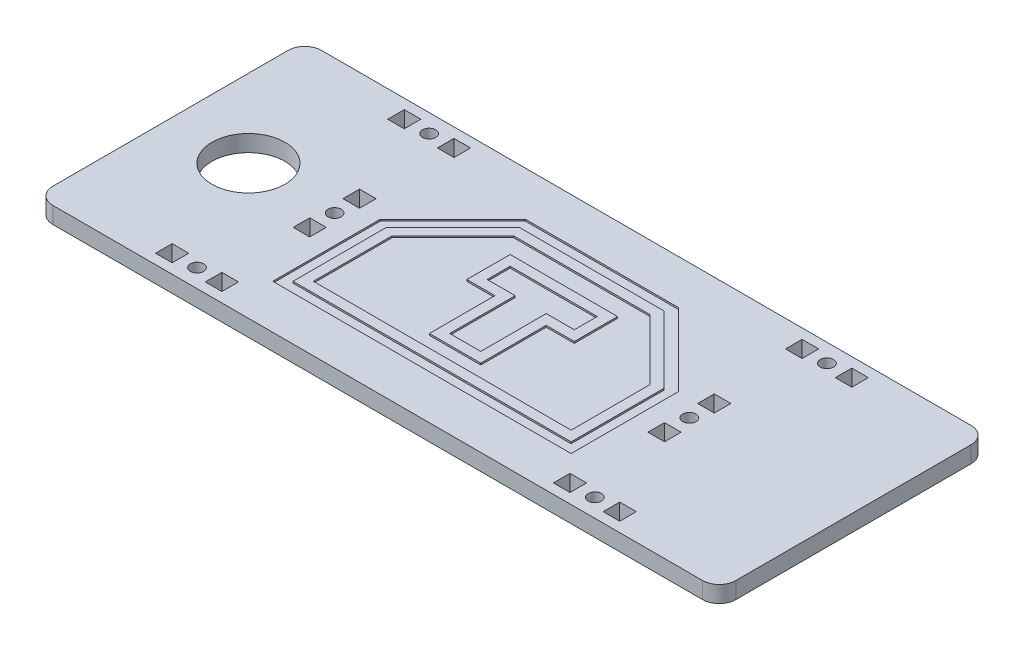
SolidWorks part; units mm, degrees
ref_plane "Front Plane" through (0, 0, 0) normal (0, 0, 1) x (1, 0, 0)
ref_plane "Top Plane" through (0, 0, 0) normal (0, 1, 0) x (1, 0, 0)
ref_plane "Right Plane" through (0, 0, 0) normal (1, 0, 0) x (0, 0, -1)
sketch "Sketch1" plane through (0, 0, 0) normal (0, 1, 0) x (1, 0, 0)
  line L0 (5.1027, 53.6563) -> (5.1027, -27.3437) construction
  line L1 (-97.8973, 53.6563) -> (108.1027, 53.6563)
  line L2 (-97.8973, 53.6563) -> (-97.8973, -27.3437)
  line L3 (-97.8973, -27.3437) -> (108.1027, -27.3437)
  line L4 (108.1027, 53.6563) -> (108.1027, -27.3437)
  line L5 (-97.8973, 13.1563) -> (108.1027, 13.1563) construction
  line L6 (60.1027, 45.6563) -> (55.1027, 45.6563)
  line L7 (-64.8973, 50.6563) -> (-59.8973, 50.6563)
  line L8 (-64.8973, 50.6563) -> (-64.8973, 45.6563)
  line L9 (-64.8973, 45.6563) -> (-59.8973, 45.6563)
  line L10 (-59.8973, 50.6563) -> (-59.8973, 45.6563)
  line L11 (-49.8973, 50.6563) -> (-44.8973, 50.6563)
  line L12 (-49.8973, 50.6563) -> (-49.8973, 45.6563)
  line L13 (-49.8973, 45.6563) -> (-44.8973, 45.6563)
  line L14 (-44.8973, 50.6563) -> (-44.8973, 45.6563)
  line L15 (55.1027, 50.6563) -> (55.1027, 45.6563)
  line L16 (60.1027, 50.6563) -> (55.1027, 50.6563)
  line L17 (60.1027, 50.6563) -> (60.1027, 45.6563)
  line L18 (70.1027, 50.6563) -> (70.1027, 45.6563)
  line L19 (75.1027, 50.6563) -> (70.1027, 50.6563)
  line L20 (75.1027, 50.6563) -> (75.1027, 45.6563)
  line L21 (75.1027, 45.6563) -> (70.1027, 45.6563)
  line L22 (75.1027, -24.3437) -> (75.1027, -19.3437)
  line L23 (75.1027, -19.3437) -> (70.1027, -19.3437)
  line L24 (75.1027, -24.3437) -> (70.1027, -24.3437)
  line L25 (70.1027, -24.3437) -> (70.1027, -19.3437)
  line L26 (60.1027, -24.3437) -> (60.1027, -19.3437)
  line L27 (60.1027, -19.3437) -> (55.1027, -19.3437)
  line L28 (55.1027, -24.3437) -> (55.1027, -19.3437)
  line L29 (60.1027, -24.3437) -> (55.1027, -24.3437)
  line L30 (-49.8973, -24.3437) -> (-44.8973, -24.3437)
  line L31 (-44.8973, -24.3437) -> (-44.8973, -19.3437)
  line L32 (-49.8973, -19.3437) -> (-44.8973, -19.3437)
  line L33 (-49.8973, -24.3437) -> (-49.8973, -19.3437)
  line L34 (-64.8973, -24.3437) -> (-59.8973, -24.3437)
  line L35 (-64.8973, -24.3437) -> (-64.8973, -19.3437)
  line L36 (-64.8973, -19.3437) -> (-59.8973, -19.3437)
  line L37 (-59.8973, -24.3437) -> (-59.8973, -19.3437)
  line L42 (-45.8973, 18.1563) -> (-45.8973, 23.1563)
  line L43 (-50.8973, 8.1563) -> (-45.8973, 8.1563)
  line L44 (-50.8973, 8.1563) -> (-50.8973, 3.1563)
  line L45 (-50.8973, 3.1563) -> (-45.8973, 3.1563)
  line L46 (-45.8973, 8.1563) -> (-45.8973, 3.1563)
  line L47 (-50.8973, 23.1563) -> (-45.8973, 23.1563)
  line L48 (-50.8973, 18.1563) -> (-50.8973, 23.1563)
  line L49 (-50.8973, 18.1563) -> (-45.8973, 18.1563)
  line L50 (56.1027, 8.1563) -> (56.1027, 3.1563)
  line L51 (61.1027, 3.1563) -> (56.1027, 3.1563)
  line L52 (61.1027, 8.1563) -> (61.1027, 3.1563)
  line L53 (61.1027, 8.1563) -> (56.1027, 8.1563)
  line L54 (56.1027, 18.1563) -> (56.1027, 23.1563)
  line L55 (61.1027, 18.1563) -> (56.1027, 18.1563)
  line L56 (61.1027, 18.1563) -> (61.1027, 23.1563)
  line L57 (61.1027, 23.1563) -> (56.1027, 23.1563)
  circle A0 centre (-54.8973, 48.1563) radius 2
  circle A1 centre (-54.8973, -21.8437) radius 2
  circle A2 centre (65.1027, -21.8437) radius 2
  circle A3 centre (65.1027, 48.1563) radius 2
  circle A5 centre (-48.3973, 13.1563) radius 2
  circle A6 centre (58.6027, 13.1563) radius 2
  circle A7 centre (-74.3973, 13.1563) radius 11
  point P36 (-59.8973, -19.3437)
  point P55 (-45.8973, 5.6563)
  dimension "D7" = 4
  dimension "D8" = 4
  dimension "D12" = 22
  dimension "D1" = 206
  dimension "D2" = 81
  dimension "D3" = 5
  dimension "D4" = 10
  dimension "D5" = 3
  dimension "D6" = 50
  dimension "D9" = 51
  dimension "D10" = 5
  dimension "D11" = 5.5
extrude "Boss-Extrude1" add sketch "Sketch1" along normal blind 5
fillet "Fillet1" radius 5 4 edges at (108.1027, 2.5, 27.3437) (-97.8973, 2.5, 27.3437) (-97.8973, 2.5, -53.6563) (108.1027, 2.5, -53.6563)
sketch "Sketch2" plane through (0, 5, 0) normal (0, 1, 0) x (1, 0, 0)
  line L0 (5.1027, 53.6563) -> (5.1027, -27.3437) construction
  line L1 (103.1027, 53.6563) -> (-92.8973, 53.6563) construction
  line L2 (-92.8973, -27.3437) -> (103.1027, -27.3437) construction
  line L3 (-97.8973, 13.1563) -> (108.1027, 13.1563) construction
  line L4 (-97.8973, 48.6563) -> (-97.8973, -22.3437) construction
  line L5 (108.1027, -22.3437) -> (108.1027, 48.6563) construction
  line L6 (-39.8973, -14.0037) -> (50.1027, -14.0037)
  line L7 (50.1027, -14.0037) -> (50.1027, 18.3963)
  line L8 (50.1027, 18.3963) -> (28.1877, 40.3113)
  line L9 (5.1027, -14.0037) -> (5.1027, -19.0236) construction
  line L10 (-39.8973, -14.0037) -> (-39.8973, 18.3963)
  line L11 (-39.8973, 18.3963) -> (-17.9823, 40.3113)
  line L12 (-17.9823, 40.3113) -> (28.1877, 40.3113)
  line L13 (47.0427, 17.1288) -> (47.0427, -10.9437)
  line L14 (47.0427, -10.9437) -> (-36.8373, -10.9437)
  line L15 (47.0427, 17.1288) -> (26.9202, 37.2513)
  line L16 (26.9202, 37.2513) -> (-16.7148, 37.2513)
  line L17 (43.9827, 15.8613) -> (43.9827, -7.8837)
  line L18 (43.9827, -7.8837) -> (-33.7773, -7.8837)
  line L19 (43.9827, 15.8613) -> (25.6527, 34.1913)
  line L20 (25.6527, 34.1913) -> (-15.4473, 34.1913)
  line L21 (-8.0373, 25.7313) -> (18.2427, 25.7313)
  line L22 (-11.0973, 28.7913) -> (21.3027, 28.7913)
  line L23 (21.3027, 28.7913) -> (21.3027, 15.7413)
  line L24 (21.3027, 15.7413) -> (12.8427, 15.7413)
  line L25 (12.8427, 15.7413) -> (12.8427, -4.0137)
  line L26 (12.8427, -4.0137) -> (-2.6373, -4.0137)
  line L27 (18.2427, 25.7313) -> (18.2427, 18.8013)
  line L28 (18.2427, 18.8013) -> (9.7827, 18.8013)
  line L29 (9.7827, 18.8013) -> (9.7827, -0.9537)
  line L30 (9.7827, -0.9537) -> (0.4227, -0.9537)
  line L31 (-33.7773, 15.8613) -> (-33.7773, -7.8837)
  line L32 (-36.8373, 17.1288) -> (-36.8373, -10.9437)
  line L33 (-33.7773, 15.8613) -> (-15.4473, 34.1913)
  line L34 (-36.8373, 17.1288) -> (-16.7148, 37.2513)
  line L35 (-11.0973, 28.7913) -> (-11.0973, 15.7413)
  line L36 (-11.0973, 15.7413) -> (-2.6373, 15.7413)
  line L37 (-2.6373, 15.7413) -> (-2.6373, -4.0137)
  line L38 (0.4227, 18.8013) -> (0.4227, -0.9537)
  line L39 (-8.0373, 18.8013) -> (0.4227, 18.8013)
  line L40 (-8.0373, 25.7313) -> (-8.0373, 18.8013)
  line L41 (5.1027, 94.6263) -> (5.1027, -14.0037)
  line L42 (-88.3154, 13.1563) -> (67.2958, 13.1563) construction
  point P25 (5.1027, 34.1913)
  point P43 (5.1027, -10.9437)
  point P44 (5.1027, -7.8837)
  point P48 (5.1027, 37.2513)
  point P49 (5.1027, 28.7913)
  point P52 (5.1027, -4.0137)
  point P53 (5.1027, -0.9537)
  point P56 (5.1027, 25.7313)
  point P59 (5.1027, 40.3113)
  dimension "D1" = 90
  dimension "D2" = 32.4
  dimension "D3" = 46.17
  dimension "D4" = 45
  dimension "D5" = 3.06
  dimension "D6" = 3.06
  dimension "D7" = 3.06
  dimension "D8" = 3.06
  dimension "D9" = 3.06
  dimension "D10" = 3.06
  dimension "D11" = 3.06
  dimension "D12" = 3.06
  dimension "D13" = 5.4
  dimension "D14" = 16.2
  dimension "D15" = 13.05
  dimension "D16" = 8.46
  dimension "D17" = 3.87
  dimension "D18" = 3.06
  dimension "D19" = 3.06
  dimension "D20" = 3.06
  dimension "D21" = 3.06
  dimension "D22" = 3.06
  dimension "D23" = 27.16
extrude "Cut-Extrude1" cut sketch "Sketch2" against normal blind 0.5 contours L41 L12 L11 L10 L6 L14 L32 L34 L16 | L12 L41 L16 L15 L13 L14 L6 L7 L8 | L20 L41 L22 L23 L24 L25 L26 L18 L17 L19 | L41 L20 L33 L31 L18 L26 L37 L36 L35 L22 | L41 L21 L40 L39 L38 L30 | L21 L41 L30 L29 L28 L27
